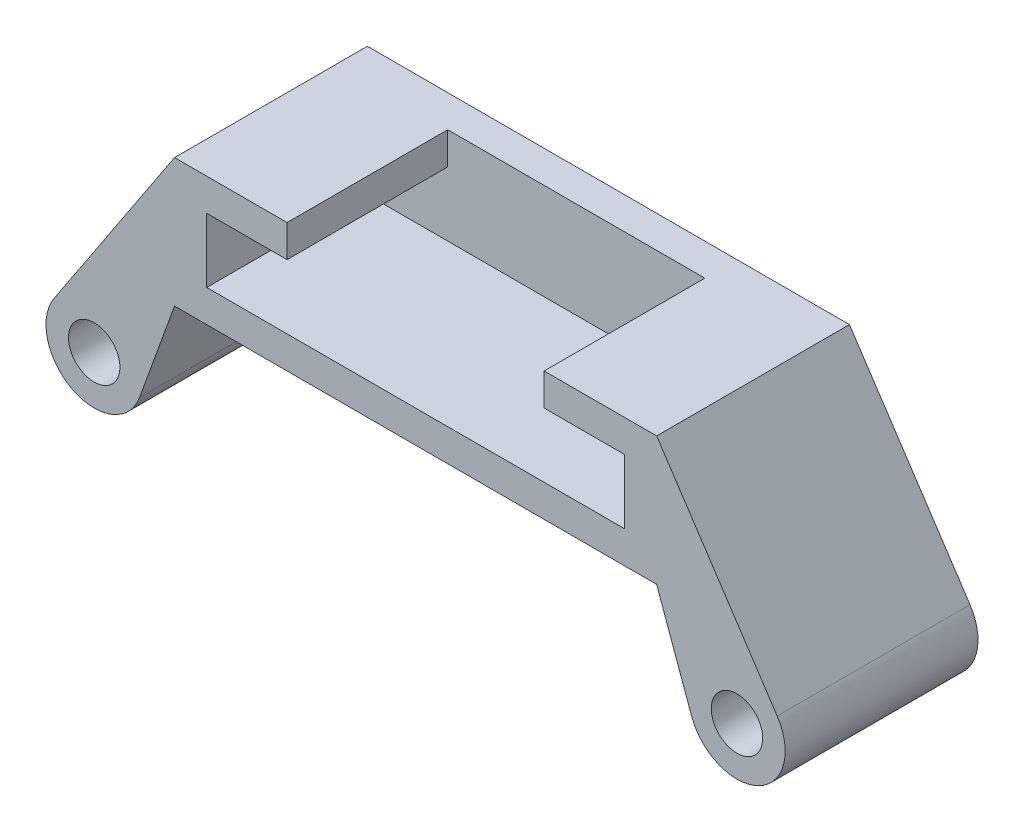
SolidWorks part; units mm, degrees
ref_plane "Спереди" through (0, 0, 0) normal (0, 0, 1) x (1, 0, 0)
ref_plane "Сверху" through (0, 0, 0) normal (0, 1, 0) x (1, 0, 0)
ref_plane "Справа" through (0, 0, 0) normal (1, 0, 0) x (0, 0, -1)
sketch "Эскиз1" plane through (0, 0, 0) normal (0, 0, 1) x (1, 0, 0)
  line L0 (-62.948, 0) -> (-22.948, 0) construction
  line L1 (-42.948, 0) -> (-42.948, 5) construction
  line L2 (-57.9479, 5) -> (-27.948, 5)
  line L3 (-27.948, 5) -> (-25.7689, -1.021)
  line L4 (-27.948, 5) -> (-27.948, 13) construction
  line L5 (-27.948, 13) -> (-20.4456, 1.6548)
  line L6 (-57.9479, 5) -> (-57.9479, 13) construction
  line L7 (-57.9479, 13) -> (-27.948, 13)
  line L8 (-57.9479, 5) -> (-60.127, -1.021)
  line L9 (-57.9479, 13) -> (-65.4503, 1.6548)
  circle A0 centre (-62.948, 0) radius 1.6
  circle A1 centre (-22.948, 0) radius 1.6
  arc A4 (-65.4503, 1.6548) -> (-60.127, -1.021) centre (-62.948, 0) ccw
  arc A5 (-25.7689, -1.021) -> (-20.4456, 1.6548) centre (-22.948, 0) ccw
  point P12 (-42.948, 5)
extrude "Бобышка-Вытянуть1" add sketch "Эскиз1" along normal blind 12
sketch "Эскиз2" plane through (0, 0, 12) normal (0, 0, 1) x (1, 0, 0)
  line L0 (-42.948, 13) -> (-34.948, 13)
  line L1 (-27.948, 13) -> (-57.9479, 13) construction
  line L2 (-42.948, 13) -> (-50.948, 13)
  line L3 (-50.948, 13) -> (-50.948, 11)
  line L4 (-34.948, 13) -> (-34.948, 11)
  line L5 (-50.948, 11) -> (-55.948, 11)
  line L6 (-55.948, 11) -> (-55.948, 7)
  line L7 (-55.948, 7) -> (-29.948, 7)
  line L8 (-29.948, 7) -> (-29.948, 11)
  line L9 (-29.948, 11) -> (-34.948, 11)
extrude "Вырез-Вытянуть1" cut sketch "Эскиз2" against normal blind 10
